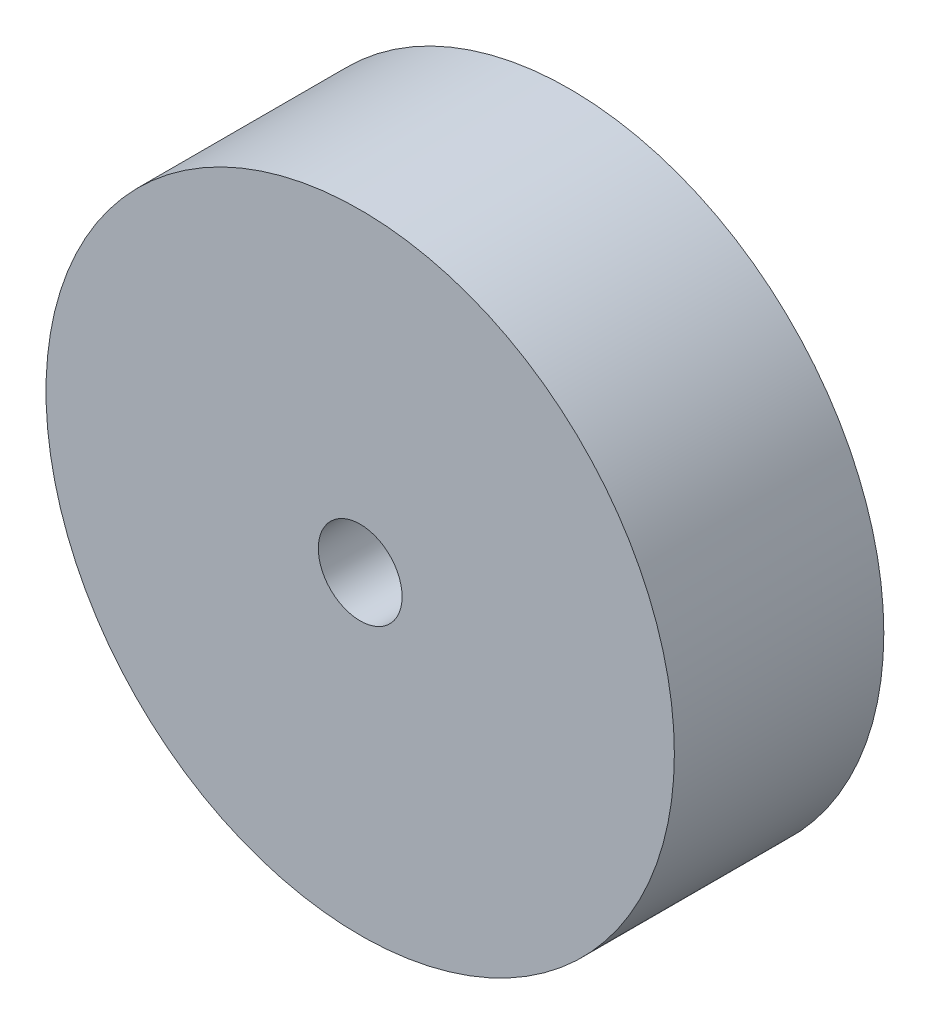
SolidWorks part; units mm, degrees
material "BUTYL"
ref_plane "前视基准面" through (0, 0, 0) normal (0, 0, 1) x (1, 0, 0)
ref_plane "上视基准面" through (0, 0, 0) normal (0, 1, 0) x (1, 0, 0)
ref_plane "右视基准面" through (0, 0, 0) normal (1, 0, 0) x (0, 0, -1)
other "Configuration Table"
sketch "草图1" plane through (0, 0, 0) normal (0, 0, 1) x (1, 0, 0)
  circle A0 centre (0, 0) radius 2
  circle A1 centre (0, 0) radius 15
  dimension "D1" = 4
  dimension "D2" = 30
extrude "凸台-拉伸1" add sketch "草图1" along normal blind 10
